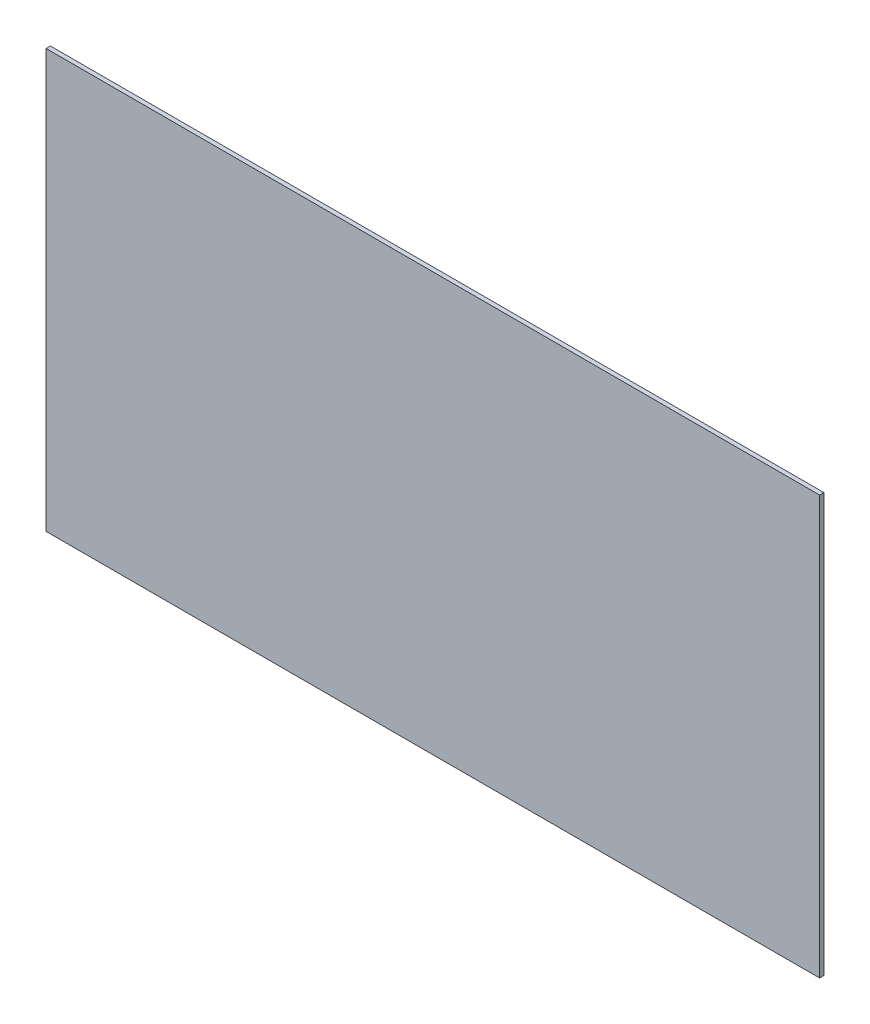
SolidWorks part; units mm, degrees
ref_plane "Front Plane" through (0, 0, 0) normal (0, 0, 1) x (1, 0, 0)
ref_plane "Top Plane" through (0, 0, 0) normal (0, 1, 0) x (1, 0, 0)
ref_plane "Right Plane" through (0, 0, 0) normal (1, 0, 0) x (0, 0, -1)
sketch "Sketch1" plane through (0, 0, 0) normal (0, 0, 1) x (1, 0, 0)
  line L1 (-11.2291, -292) -> (-551.2291, -292)
  line L2 (-11.2291, -292) -> (-11.2291, 0)
  line L3 (-11.2291, 0) -> (-551.2291, 0)
  line L4 (-551.2291, -292) -> (-551.2291, 0)
extrude "Boss-Extrude1" add sketch "Sketch1" along normal blind 3
